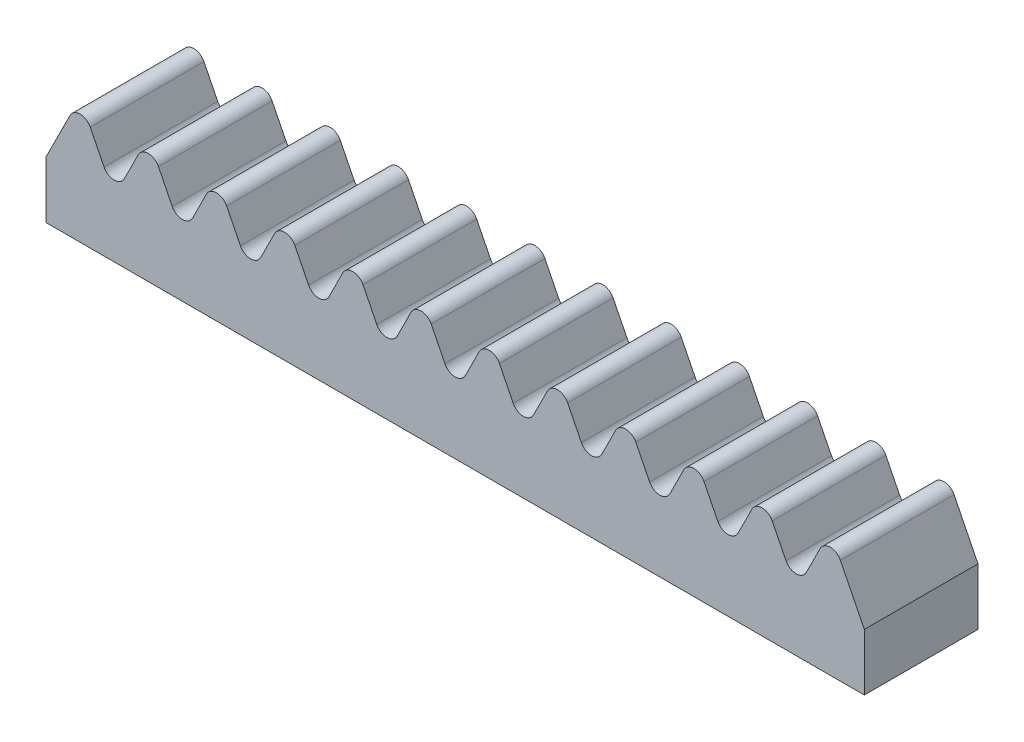
SolidWorks part; units mm, degrees
material "ABS"
ref_plane "Front Plane" through (0, 0, 0) normal (0, 0, 1) x (1, 0, 0)
ref_plane "Top Plane" through (0, 0, 0) normal (0, 1, 0) x (1, 0, 0)
ref_plane "Right Plane" through (0, 0, 0) normal (1, 0, 0) x (0, 0, -1)
sketch "Sketch2" plane through (0, 0, 0) normal (0, 0, 1) x (1, 0, 0)
  line L0 (-18, 0) -> (18, 0)
  line L1 (-18, 0) -> (-18, 2.5)
  line L2 (18, 0) -> (18, 2.5)
  line L7 (-14.5528, 3.3944) -> (-13.9472, 4.6056)
  line L8 (-18, 2.5) -> (-16.9472, 4.6056)
  line L9 (-15.4472, 3.3944) -> (-16.0528, 4.6056)
  line L10 (-12.4472, 3.3944) -> (-13.0528, 4.6056)
  line L11 (-11.5528, 3.3944) -> (-10.9472, 4.6056)
  line L12 (-9.4472, 3.3944) -> (-10.0528, 4.6056)
  line L13 (-8.5528, 3.3944) -> (-7.9472, 4.6056)
  line L14 (-6.4472, 3.3944) -> (-7.0528, 4.6056)
  line L15 (-5.5528, 3.3944) -> (-4.9472, 4.6056)
  line L16 (-3.4472, 3.3944) -> (-4.0528, 4.6056)
  line L17 (-2.5528, 3.3944) -> (-1.9472, 4.6056)
  line L18 (-0.4472, 3.3944) -> (-1.0528, 4.6056)
  line L19 (0.4472, 3.3944) -> (1.0528, 4.6056)
  line L20 (2.5528, 3.3944) -> (1.9472, 4.6056)
  line L21 (3.4472, 3.3944) -> (4.0528, 4.6056)
  line L22 (5.5528, 3.3944) -> (4.9472, 4.6056)
  line L23 (6.4472, 3.3944) -> (7.0528, 4.6056)
  line L24 (8.5528, 3.3944) -> (7.9472, 4.6056)
  line L25 (9.4472, 3.3944) -> (10.0528, 4.6056)
  line L26 (11.5528, 3.3944) -> (10.9472, 4.6056)
  line L27 (12.4472, 3.3944) -> (13.0528, 4.6056)
  line L28 (14.5528, 3.3944) -> (13.9472, 4.6056)
  line L29 (15.4472, 3.3944) -> (16.0528, 4.6056)
  line L30 (18, 2.5) -> (16.9472, 4.6056)
  arc A0 (-16.9472, 4.6056) -> (-16.0528, 4.6056) centre (-16.5, 4.382) cw
  arc A1 (-13.9472, 4.6056) -> (-13.0528, 4.6056) centre (-13.5, 4.382) cw
  arc A2 (-10.9472, 4.6056) -> (-10.0528, 4.6056) centre (-10.5, 4.382) cw
  arc A3 (-7.9472, 4.6056) -> (-7.0528, 4.6056) centre (-7.5, 4.382) cw
  arc A4 (-4.9472, 4.6056) -> (-4.0528, 4.6056) centre (-4.5, 4.382) cw
  arc A5 (-1.9472, 4.6056) -> (-1.0528, 4.6056) centre (-1.5, 4.382) cw
  arc A6 (1.0528, 4.6056) -> (1.9472, 4.6056) centre (1.5, 4.382) cw
  arc A7 (4.0528, 4.6056) -> (4.9472, 4.6056) centre (4.5, 4.382) cw
  arc A8 (7.0528, 4.6056) -> (7.9472, 4.6056) centre (7.5, 4.382) cw
  arc A9 (10.0528, 4.6056) -> (10.9472, 4.6056) centre (10.5, 4.382) cw
  arc A10 (13.0528, 4.6056) -> (13.9472, 4.6056) centre (13.5, 4.382) cw
  arc A11 (16.0528, 4.6056) -> (16.9472, 4.6056) centre (16.5, 4.382) cw
  arc A12 (14.5528, 3.3944) -> (15.4472, 3.3944) centre (15, 3.618) ccw
  arc A13 (11.5528, 3.3944) -> (12.4472, 3.3944) centre (12, 3.618) ccw
  arc A14 (8.5528, 3.3944) -> (9.4472, 3.3944) centre (9, 3.618) ccw
  arc A15 (5.5528, 3.3944) -> (6.4472, 3.3944) centre (6, 3.618) ccw
  arc A16 (2.5528, 3.3944) -> (3.4472, 3.3944) centre (3, 3.618) ccw
  arc A17 (-0.4472, 3.3944) -> (0.4472, 3.3944) centre (0, 3.618) ccw
  arc A18 (-3.4472, 3.3944) -> (-2.5528, 3.3944) centre (-3, 3.618) ccw
  arc A19 (-6.4472, 3.3944) -> (-5.5528, 3.3944) centre (-6, 3.618) ccw
  arc A20 (-9.4472, 3.3944) -> (-8.5528, 3.3944) centre (-9, 3.618) ccw
  arc A21 (-12.4472, 3.3944) -> (-11.5528, 3.3944) centre (-12, 3.618) ccw
  arc A22 (-14.5528, 3.3944) -> (-15.4472, 3.3944) centre (-15, 3.618) cw
  point P4 (0, 0)
  dimension "D1" = 0.5
  dimension "D3" = 0.5
  dimension "D2" = 12
extrude "Boss-Extrude1" add sketch "Sketch2" along normal blind 5
